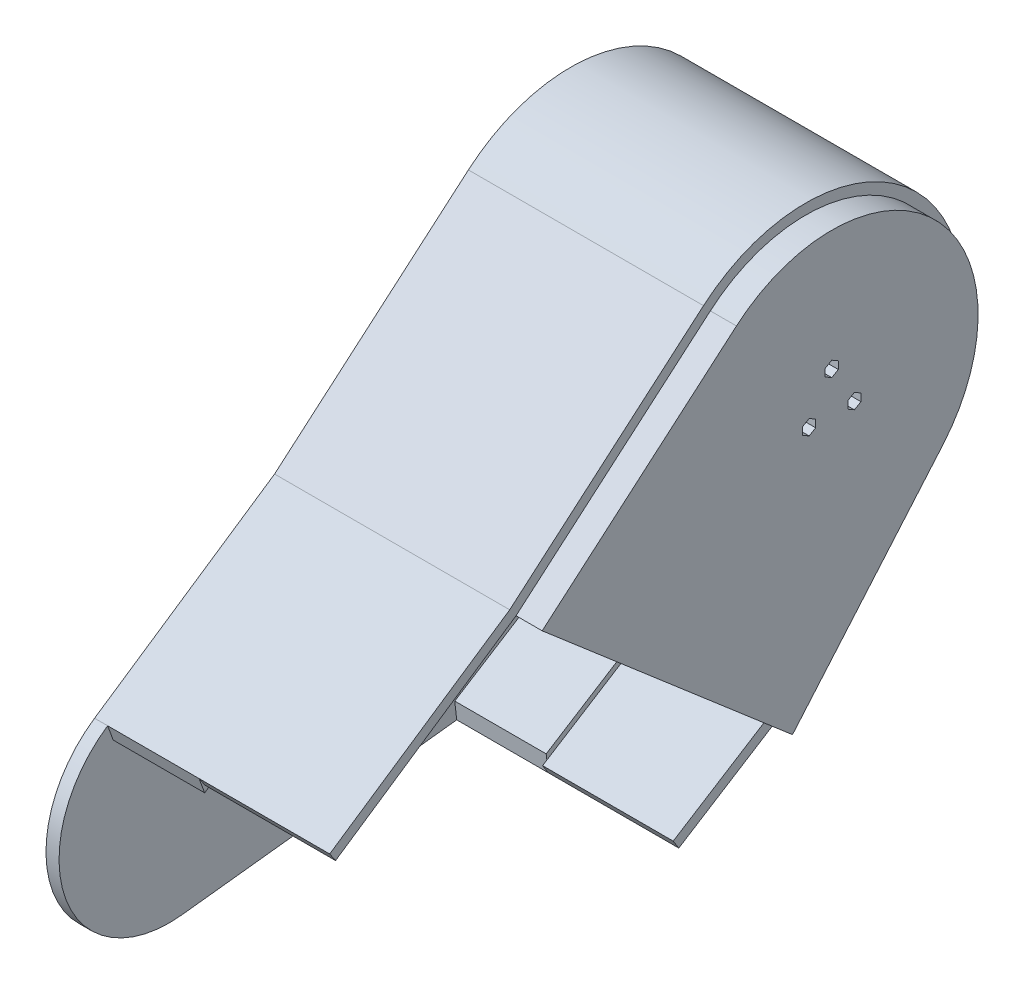
SolidWorks part; units mm, degrees
ref_plane "前视基准面" through (0, 0, 0) normal (0, 0, 1) x (1, 0, 0)
ref_plane "上视基准面" through (0, 0, 0) normal (0, 1, 0) x (1, 0, 0)
ref_plane "右视基准面" through (0, 0, 0) normal (1, 0, 0) x (0, 0, -1)
other "Configuration Table"
sketch "草图3" plane through (0, 0, 0) normal (1, 0, 0) x (0, 0, -1)
  line L5 (-39.0958, 45.5139) -> (-113.2844, -18.213)
  line L6 (-113.2844, -18.213) -> (-182.19, -64.6979)
  line L7 (45.5951, -39.0011) -> (-12.3895, -106.7893)
  line L8 (-12.3895, -106.7893) -> (-48.563, -129.5652)
  line L9 (-48.563, -129.5652) -> (-153.7955, -141.6028)
  arc A2 (45.5951, -39.0011) -> (-39.0958, 45.5139) centre (0, 0) ccw
  arc A3 (-182.19, -64.6979) -> (-153.7955, -141.6028) centre (-158.5911, -99.6791) ccw
  dimension "D1" = 60
extrude "凸台-拉伸1" add sketch "草图3" along normal blind 40
sketch "草图6" plane through (40, 0, 0) normal (1, 0, 0) x (0, 0, -1)
  line L27 (-35.1862, 40.9625) -> (-109.6395, -22.9918)
  line L28 (-109.6395, -22.9918) -> (-178.8345, -69.6718)
  line L29 (-154.4774, -135.6416) -> (-50.603, -123.7594)
  line L30 (-50.603, -123.7594) -> (-16.3571, -102.1971)
  line L31 (-16.3571, -102.1971) -> (41.0356, -35.101)
  line L32 (-35.1862, 40.9625) -> (-109.6395, -22.9918)
  line L33 (-109.6395, -22.9918) -> (-178.8345, -69.6718)
  line L34 (-154.4774, -135.6416) -> (-50.603, -123.7594)
  line L35 (-50.603, -123.7594) -> (-16.3571, -102.1971)
  line L36 (-16.3571, -102.1971) -> (41.0356, -35.101)
  arc A11 (-178.8345, -69.6718) -> (-154.4774, -135.6416) centre (-158.5911, -99.6791) ccw
  arc A12 (41.0356, -35.101) -> (-35.1862, 40.9625) centre (0, 0) ccw
  arc A13 (-178.8345, -69.6718) -> (-154.4774, -135.6416) centre (-158.5911, -99.6791) ccw
  arc A14 (41.0356, -35.101) -> (-35.1862, 40.9625) centre (0, 0) ccw
  dimension "D2" = 6
extrude "切除-拉伸4" cut sketch "草图6" against normal blind 35
sketch "草图7" plane through (0, -122.4083, -14.0023) normal (0, -0.9935, -0.1136) x (-1, 0, 0)
  line L0 (-40, -62.9733) -> (0, -62.9733) construction
  line L1 (-40, -168.8921) -> (-5, -168.8921)
  line L2 (-40, -168.8921) -> (-40, -62.9733)
  line L3 (-40, -62.9733) -> (-5, -62.9733)
  line L4 (-5, -168.8921) -> (-5, -62.9733)
  dimension "D1" = 35
extrude "切除-拉伸5" cut sketch "草图7" against normal blind 15
sketch "草图9" plane through (0, 0, 0) normal (1, 0, 0) x (0, 0, -1)
  line L0 (-182.19, -64.6979) -> (-153.7955, -141.6028)
  arc A2 (-182.19, -64.6979) -> (-153.7955, -141.6028) centre (-158.5911, -99.6791) ccw construction
  arc A3 (-182.19, -64.6979) -> (-153.7955, -141.6028) centre (-158.5911, -99.6791) ccw
ref_plane "基准面2" through (40, 0, 0) normal (1, 0, 0) x (0, 0, -1)
sketch "草图10" plane through (40, 0, 0) normal (1, 0, 0) x (0, 0, -1)
  line L0 (-182.19, -64.6979) -> (-153.7955, -141.6028) construction
  line L1 (-182.19, -64.6979) -> (-153.7955, -141.6028)
  arc A0 (-182.19, -64.6979) -> (-153.7955, -141.6028) centre (-158.5911, -99.6791) ccw construction
  arc A1 (-182.19, -64.6979) -> (-153.7955, -141.6028) centre (-158.5911, -99.6791) ccw
extrude "切除-拉伸9" cut sketch "草图10" against normal blind 35
sketch "草图11" plane through (40, 0, 0) normal (1, 0, 0) x (0, 0, -1)
  line L0 (-153.7955, -141.6028) -> (-155.9456, -135.7793) construction
  line L1 (-154.4774, -135.6416) -> (-153.7955, -141.6028) construction
  line L2 (-153.7955, -141.6028) -> (-155.9456, -135.7793)
  line L3 (-154.4774, -135.6416) -> (-153.7955, -141.6028)
  arc A0 (-155.9456, -135.7793) -> (-154.4774, -135.6416) centre (-158.5911, -99.6791) ccw construction
  arc A1 (-155.9456, -135.7793) -> (-154.4774, -135.6416) centre (-158.5911, -99.6791) ccw
extrude "切除-拉伸10" cut sketch "草图11" against normal blind 35
sketch "草图12" plane through (0, 0, 0) normal (-1, 0, 0) x (0, 0, 1)
  arc A1 (88.8563, -93.6577) -> (113.9696, -97.7907) centre (103.4794, -83.1675) ccw construction
  arc A2 (84.7935, -96.5722) -> (116.8841, -101.8534) centre (103.4794, -83.1675) ccw
  arc A3 (92.919, -90.7432) -> (111.0551, -93.7279) centre (103.4794, -83.1675) ccw
  arc A4 (92.919, -90.7432) -> (84.7935, -96.5722) centre (88.8563, -93.6577) ccw
  arc A5 (116.8841, -101.8534) -> (111.0551, -93.7279) centre (113.9696, -97.7907) ccw
  point P5 (100.557, -100.9253)
  dimension "D1" = 5
extrude "切除-拉伸11" cut sketch "草图12" against normal blind 10
ref_plane "基准面3" through (40, 0, 0) normal (1, 0, 0) x (0, 0, -1)
sketch "草图14" plane through (40, 0, 0) normal (1, 0, 0) x (0, 0, -1)
  line L0 (-49.3195, -122.9513) -> (-16.3571, -102.1971) construction
  line L1 (-48.563, -129.5652) -> (-12.3895, -106.7893) construction
  line L2 (-49.3195, -122.9513) -> (-16.3571, -102.1971) construction
  line L3 (-12.3895, -106.7893) -> (45.5951, -39.0011) construction
  line L4 (-16.3571, -102.1971) -> (41.0356, -35.101) construction
  line L5 (-35.1862, 40.9625) -> (-109.6395, -22.9918) construction
  line L6 (-39.0958, 45.5139) -> (-113.2844, -18.213) construction
  line L7 (-109.6395, -22.9918) -> (-178.8345, -69.6718) construction
  line L8 (-113.2844, -18.213) -> (-182.19, -64.6979) construction
  line L9 (-49.3195, -122.9513) -> (-16.3571, -102.1971)
  line L10 (-48.563, -129.5652) -> (-12.3895, -106.7893)
  line L11 (-49.3195, -122.9513) -> (-16.3571, -102.1971)
  line L12 (-12.3895, -106.7893) -> (45.5951, -39.0011)
  line L13 (-16.3571, -102.1971) -> (41.0356, -35.101)
  line L14 (-35.1862, 40.9625) -> (-109.6395, -22.9918)
  line L15 (-39.0958, 45.5139) -> (-113.2844, -18.213)
  line L16 (-109.6395, -22.9918) -> (-178.8345, -69.6718)
  line L17 (-113.2844, -18.213) -> (-182.19, -64.6979)
  line L18 (41.0356, -35.101) -> (-16.3571, -102.1971)
  arc A0 (41.0356, -35.101) -> (-35.1862, 40.9625) centre (0, 0) ccw construction
  arc A1 (45.5951, -39.0011) -> (-39.0958, 45.5139) centre (0, 0) ccw construction
  arc A2 (41.0356, -35.101) -> (-35.1862, 40.9625) centre (0, 0) ccw
  arc A3 (45.5951, -39.0011) -> (-39.0958, 45.5139) centre (0, 0) ccw
extrude "拉伸-薄壁1" add sketch "草图14" along normal blind 50 thin contours L10 L12 A3 L15 L17 thin type one direction reverse wall 4
ref_plane "基准面4" through (90, 0, 0) normal (1, 0, 0) x (0, 0, -1)
sketch "草图15" plane through (90, 0, 0) normal (1, 0, 0) x (0, 0, -1)
  line L0 (-15.0346, -103.7279) -> (42.5554, -36.401) construction
  line L1 (-36.4894, 42.4797) -> (-110.8545, -21.3988) construction
  line L2 (-15.0346, -103.7279) -> (42.5554, -36.401)
  line L3 (-36.4894, 42.4797) -> (-110.8545, -21.3988)
  line L4 (-110.8545, -21.3988) -> (-15.0346, -103.7279)
  arc A0 (42.5554, -36.401) -> (-36.4894, 42.4797) centre (0, 0) ccw construction
  arc A1 (42.5554, -36.401) -> (-36.4894, 42.4797) centre (0, 0) ccw
extrude "凸台-拉伸2" add sketch "草图15" along normal blind 10 separate body
sketch "草图16" plane through (100, 0, 0) normal (1, 0, 0) x (0, 0, -1)
  line L30 (6.1603, -3.5566) -> (6.1603, -6.4434)
  line L31 (0, 7.1132) -> (2.5, 8.5566)
  line L32 (2.5, 8.5566) -> (2.5, 11.4434)
  line L33 (2.5, 11.4434) -> (0, 12.8868)
  line L34 (0, 12.8868) -> (-2.5, 11.4434)
  line L35 (-2.5, 11.4434) -> (-2.5, 8.5566)
  line L36 (-2.5, 8.5566) -> (0, 7.1132)
  line L37 (6.1603, -6.4434) -> (8.6603, -7.8868)
  line L38 (8.6603, -7.8868) -> (11.1603, -6.4434)
  line L39 (11.1603, -6.4434) -> (11.1603, -3.5566)
  line L40 (11.1603, -3.5566) -> (8.6603, -2.1132)
  line L41 (8.6603, -2.1132) -> (6.1603, -3.5566)
  line L42 (-6.1603, -3.5566) -> (-8.6603, -2.1132)
  line L43 (-8.6603, -2.1132) -> (-11.1603, -3.5566)
  line L44 (-11.1603, -3.5566) -> (-11.1603, -6.4434)
  line L45 (-11.1603, -6.4434) -> (-8.6603, -7.8868)
  line L46 (-8.6603, -7.8868) -> (-6.1603, -6.4434)
  line L47 (-6.1603, -6.4434) -> (-6.1603, -3.5566)
  circle A0 centre (0, 10) radius 2.5 construction
  point P23 (0, 0)
  point P36 (0, 0)
  dimension "D1" = 5
  dimension "D2" = 10
  dimension "D3" = 3
extrude "切除-拉伸12" cut sketch "草图16" against normal blind 5
